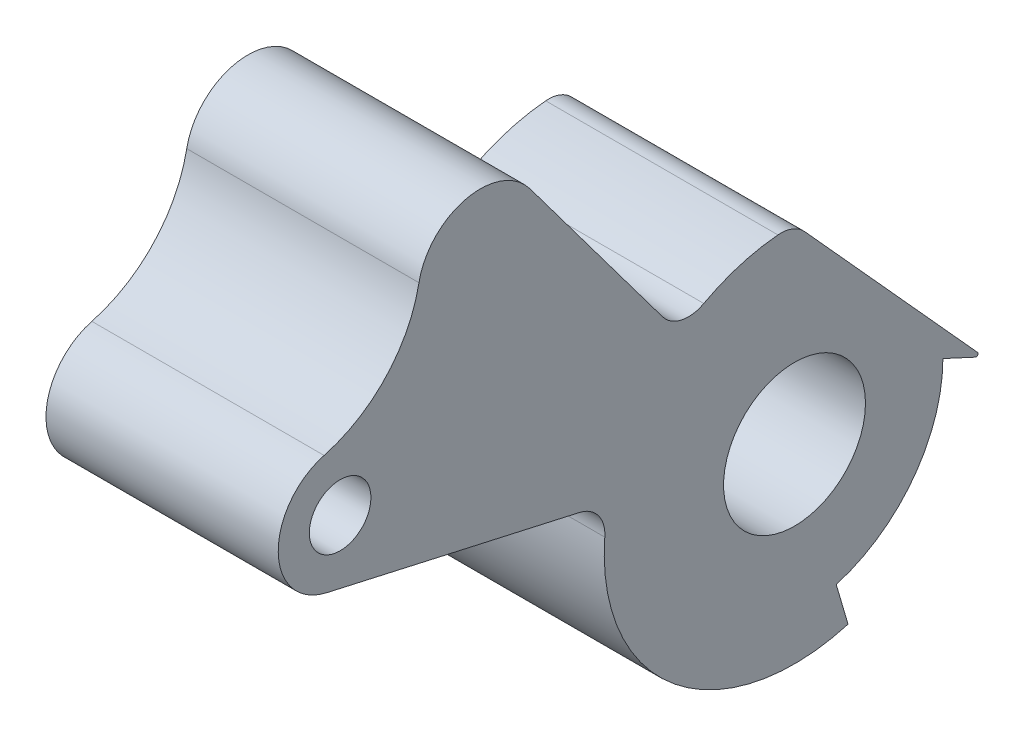
SolidWorks part; units mm, degrees
ref_plane "Front Plane" through (0, 0, 0) normal (0, 0, 1) x (1, 0, 0)
ref_plane "Top Plane" through (0, 0, 0) normal (0, 1, 0) x (1, 0, 0)
ref_plane "Right Plane" through (0, 0, 0) normal (1, 0, 0) x (0, 0, -1)
sketch "Sketch1" plane through (0, 0, 0) normal (1, 0, 0) x (0, 0, -1)
  line L0 (5.842, 0) -> (7.4557, -0.7464)
  line L1 (7.4557, -0.7464) -> (0, 7.493)
  line L2 (1.6426, -5.6063) -> (3.2852, -11.2126)
  line L3 (-4.4894, 5.9992) -> (-10.4106, 13.9119)
  line L5 (-18.4274, 4.147) -> (-7.3102, 1.6451)
  circle A0 centre (0, 0) radius 2.794
  circle A1 centre (0, 0) radius 5.842
  circle A2 centre (0, 0) radius 7.493
  circle A3 centre (0, 0) radius 11.684
  arc A4 (-18.4274, 4.147) -> (-18.5237, 8.8799) centre (-17.8922, 6.5253) cw
  arc A5 (-10.4106, 13.9119) -> (-14.7875, 12.9013) centre (-12.3761, 12.441) ccw
  arc A6 (-18.5237, 8.8799) -> (-14.7875, 12.9013) centre (-19.8621, 13.8698) ccw
  circle A7 centre (-17.8922, 6.5253) radius 1.2125
  dimension "D1" = 5.588
  dimension "D2" = 11.684
  dimension "D3" = 14.986
  dimension "D4" = 23.368
  dimension "D5" = 5.842
  dimension "D6" = 1.778
extrude "Boss-Extrude1" add sketch "Sketch1" along normal blind 9.144
fillet "Fillet1" radius 0.0762 1 edges at (4.572, -0.7464, -7.4557)
fillet "Fillet2" radius 1.27 1 edges at (4.572, 5.9992, 4.4894)
fillet "Fillet3" radius 1.27 1 edges at (4.572, 7.493, 0)
fillet "Fillet4" radius 1.27 1 edges at (4.572, 1.6451, 7.3102)
